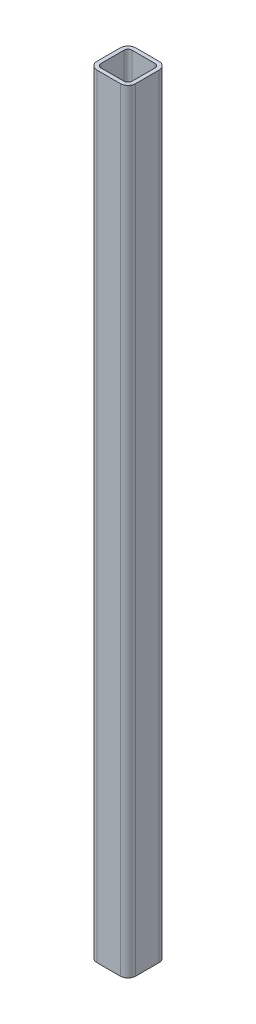
SolidWorks part; units mm, degrees
ref_plane "Front Plane" through (0, 0, 0) normal (0, 0, 1) x (1, 0, 0)
ref_plane "Top Plane" through (0, 0, 0) normal (0, 1, 0) x (1, 0, 0)
ref_plane "Right Plane" through (0, 0, 0) normal (1, 0, 0) x (0, 0, -1)
sketch "Sketch1" plane through (0, 0, 0) normal (1, 0, 0) x (0, 0, -1)
  line L0 (0, 0) -> (0, -800)
other "Square tube 40 X 40 X 4(1)"
ref_plane "Plane1" through (0, 0, 0) normal (0, -1, 0) x (0, 0, -1)
sketch "Sketch11" plane through (0, 0, 0) normal (0, -1, 0) x (0, 0, -1)
  line L0 (-12, -16) -> (12, -16)
  line L1 (-16, -12) -> (-16, 12)
  line L2 (12, 16) -> (-12, 16)
  line L3 (16, 12) -> (16, -12)
  line L4 (-12, -20) -> (12, -20)
  line L5 (-20, -12) -> (-20, 12)
  line L6 (12, 20) -> (-12, 20)
  line L7 (20, 12) -> (20, -12)
  arc A0 (20, 12) -> (12, 20) centre (12, 12) ccw
  arc A1 (12, -20) -> (20, -12) centre (12, -12) ccw
  arc A2 (-20, -12) -> (-12, -20) centre (-12, -12) ccw
  arc A3 (-12, 20) -> (-20, 12) centre (-12, 12) ccw
  arc A4 (-12, 16) -> (-16, 12) centre (-12, 12) ccw
  arc A5 (16, 12) -> (12, 16) centre (12, 12) ccw
  arc A6 (12, -16) -> (16, -12) centre (12, -12) ccw
  arc A7 (-16, -12) -> (-12, -16) centre (-12, -12) ccw
  point P0 (-20, 0)
  point P1 (20, 0)
  point P2 (0, 20)
  point P3 (0, -20)
  point P4 (0, 0)
  point P5 (-20, -20)
  point P6 (20, -20)
  point P7 (20, 20)
  point P8 (-20, 20)
  point P33 (0, 0)
  dimension "D1" = 8
  dimension "Thickness" = 4
  dimension "V_leg" = 40
